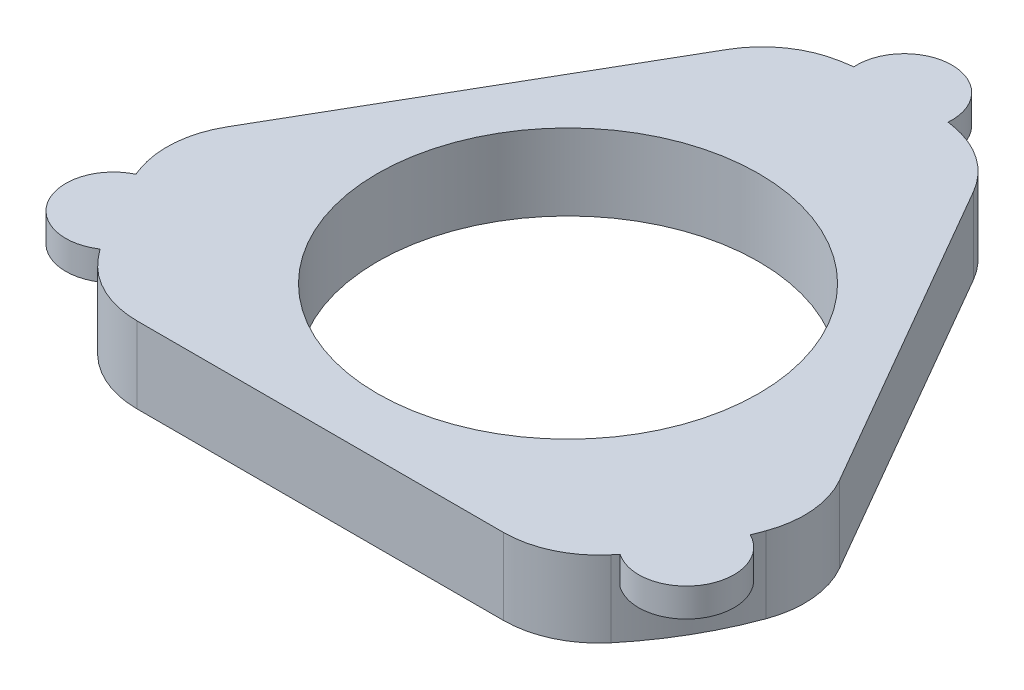
SolidWorks part; units mm, degrees
ref_plane "Спереди" through (0, 0, 0) normal (0, 0, 1) x (1, 0, 0)
ref_plane "Сверху" through (0, 0, 0) normal (0, 1, 0) x (1, 0, 0)
ref_plane "Справа" through (0, 0, 0) normal (1, 0, 0) x (0, 0, -1)
sketch "Sketch1" plane through (0, 0, 0) normal (0, 1, 0) x (1, 0, 0)
  circle A0 centre (0, 0) radius 20
  dimension "D1" = 40
extrude "Boss-Extrude1" add sketch "Sketch1" along normal blind 3.5
sketch "Sketch2" plane through (0, 0, 0) normal (0, 1, 0) x (1, 0, 0)
  circle A0 centre (0, 0) radius 35
  circle A1 centre (0, 0) radius 20
  circle A2 centre (0, 0) radius 29 construction
  circle A3 centre (0, 29) radius 2.8
  circle A4 centre (25.1147, -14.5) radius 2.8
  circle A5 centre (-25.1147, -14.5) radius 2.8
  point P16 (0, 0)
  dimension "D2" = 58
  dimension "D3" = 40
  dimension "D4" = 70
  dimension "D1" = 3
extrude "Boss-Extrude2" add sketch "Sketch2" along normal blind 8
sketch "Sketch4" plane through (0, 0, 0) normal (0, -1, 0) x (1, 0, 0)
  circle A0 centre (-25.1147, 14.5) radius 2.9
  circle A1 centre (25.1147, 14.5) radius 2.9
  circle A2 centre (0, -29) radius 2.9
  point P9 (0, 0)
  dimension "D1" = 3
extrude "Boss-Extrude3" add sketch "Sketch4" along normal blind 2 and the other way up to surface (8 mm away) other way up to face at (25.1147, 8, 17.3)
sketch "Sketch5" plane through (0, 8, 0) normal (0, 1, 0) x (1, 0, 0)
  circle A0 centre (-30.4536, -17.2504) radius 5
  circle A1 centre (0, 0) radius 35 construction
  circle A2 centre (0.2875, 34.9988) radius 5
  circle A3 centre (30.1661, -17.7484) radius 5
  point P10 (0, 0)
  dimension "D1" = 3
extrude "Boss-Extrude4" add sketch "Sketch5" against normal blind 3
sketch "Sketch3" plane through (0, 3.5, 0) normal (0, 1, 0) x (1, 0, 0)
  circle A0 centre (0, 0) radius 20
extrude "Cut-Extrude1" cut sketch "Sketch3" against normal blind 10
sketch "Sketch9" plane through (0, 8, 0) normal (0, 1, 0) x (1, 0, 0)
  circle A0 centre (0, 0) radius 18.5
extrude "Boss-Extrude5" add sketch "Sketch9" against normal blind 3.5 separate body
sketch "Sketch10" plane through (0, 4.5, 0) normal (0, -1, 0) x (-1, 0, 0)
  circle A0 centre (0, 0) radius 18.5
  circle A1 centre (0, 0) radius 17.5
  dimension "D1" = 1
  dimension "D2" = 35
extrude "Boss-Extrude6" add sketch "Sketch10" along normal blind 3.5
sketch "Sketch11" plane through (0, 8, 0) normal (0, 1, 0) x (1, 0, 0)
  line L0 (19.9463, -10.3613) -> (14.2313, -7.0617)
  line L1 (-1, 22.4546) -> (1, 22.4546)
  line L2 (-1, 22.4546) -> (-1, 15.8555)
  line L3 (-1, 15.8555) -> (1, 15.8555)
  line L4 (1, 22.4546) -> (1, 15.8555)
  line L5 (-1, 22.4546) -> (1, 15.8555) construction
  line L6 (-1, 15.8555) -> (1, 22.4546) construction
  line L7 (19.9463, -10.3613) -> (18.9463, -12.0933)
  line L8 (18.9463, -12.0933) -> (13.2313, -8.7938)
  line L9 (14.2313, -7.0617) -> (13.2313, -8.7938)
  line L10 (-18.9463, -12.0933) -> (-13.2313, -8.7938)
  line L11 (-18.9463, -12.0933) -> (-19.9463, -10.3613)
  line L12 (-19.9463, -10.3613) -> (-14.2313, -7.0617)
  line L13 (-13.2313, -8.7938) -> (-14.2313, -7.0617)
  point P0 (0, 19.1551)
  point P15 (0, 0)
  dimension "D1" = 3
extrude "Boss-Extrude7" add sketch "Sketch11" against normal blind 2
sketch "Sketch12" plane through (0, 8, 0) normal (0, 1, 0) x (1, 0, 0)
  line L1 (0, 52) -> (-45.0333, -26)
  line L2 (-45.0333, -26) -> (45.0333, -26)
  line L3 (45.0333, -26) -> (0, 52)
  circle A0 centre (0, 0) radius 26 construction
  circle A1 centre (0, 0) radius 72.1359
extrude "Cut-Extrude2" cut sketch "Sketch12" against normal blind 22
fillet "Fillet1" radius 10 6 edges at (-23.4307, 4, 26) (23.4307, 4, 26) (-10.8013, 4, -33.2916) (-34.232, 4, 7.2916) (34.232, 4, 7.2916) (10.8013, 4, -33.2916)
sketch "Sketch13" plane through (0, 8, 0) normal (0, 1, 0) x (1, 0, 0)
  circle A0 centre (0, 0) radius 20
extrude "Cut-Extrude3" cut sketch "Sketch13" against normal blind 10
